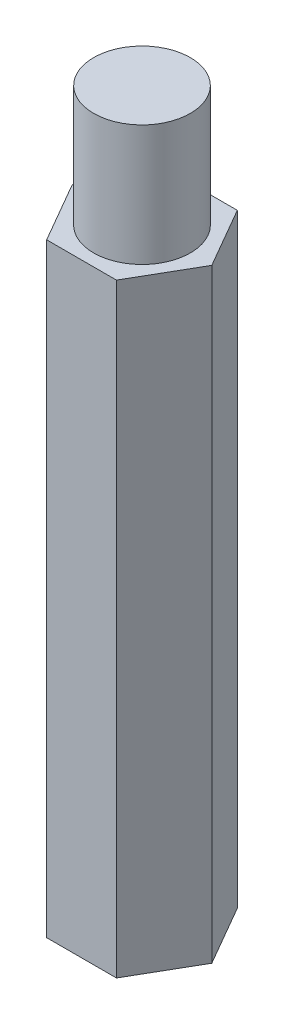
SolidWorks part; units mm, degrees
ref_plane "前视基准面" through (0, 0, 0) normal (0, 0, 1) x (1, 0, 0)
ref_plane "上视基准面" through (0, 0, 0) normal (0, 1, 0) x (1, 0, 0)
ref_plane "右视基准面" through (0, 0, 0) normal (1, 0, 0) x (0, 0, -1)
other "Configuration Table"
sketch "草图1" plane through (0, 0, 0) normal (0, 1, 0) x (1, 0, 0)
  line L0 (1.1547, -2) -> (2.3094, 0)
  line L1 (1.1547, 2) -> (-1.1547, 2)
  line L2 (-1.1547, 2) -> (-2.3094, 0)
  line L3 (-2.3094, 0) -> (-1.1547, -2)
  line L4 (-1.1547, -2) -> (1.1547, -2)
  line L5 (2.3094, 0) -> (1.1547, 2)
  circle A0 centre (0, 0) radius 2 construction
  dimension "D1" = 4
extrude "凸台-拉伸1" add sketch "草图1" along normal blind 20
sketch "草图2" plane through (0, 20, 0) normal (0, 1, 0) x (1, 0, 0)
  circle A0 centre (0, 0) radius 1.6
extrude "凸台-拉伸2" add sketch "草图2" along normal blind 4
sketch "草图3" plane through (0, 0, 0) normal (0, -1, 0) x (1, 0, 0)
  circle A0 centre (0, 0) radius 1.6
extrude "切除-拉伸1" cut sketch "草图3" against normal blind 4
